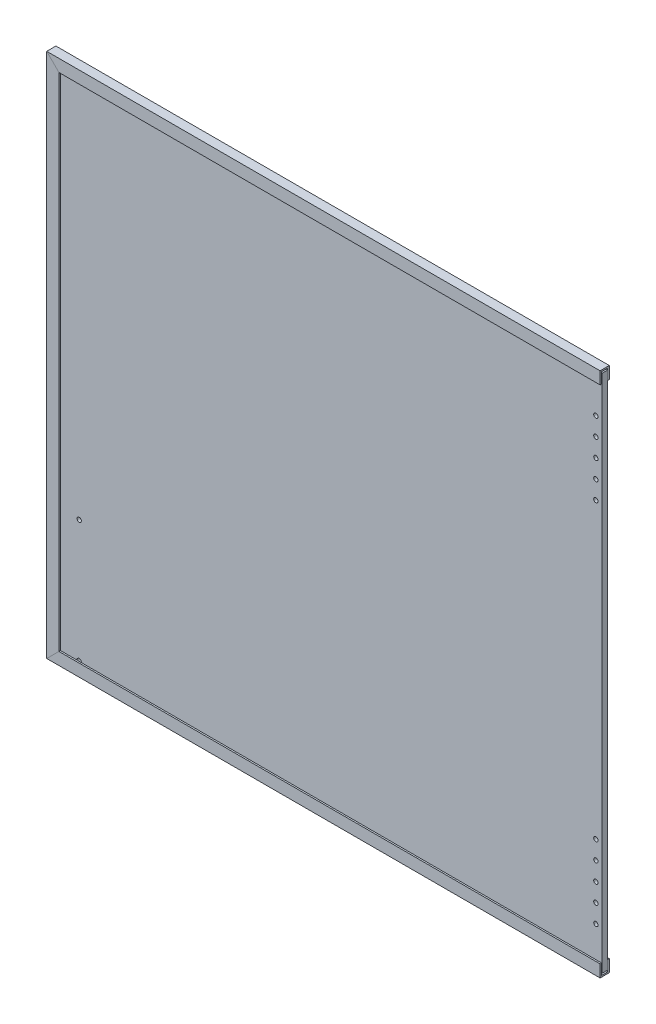
SolidWorks part; units mm, degrees
material "PC High Viscosity"
ref_plane "Front Plane" through (0, 0, 0) normal (0, 0, 1) x (1, 0, 0)
ref_plane "Top Plane" through (0, 0, 0) normal (0, 1, 0) x (1, 0, 0)
ref_plane "Right Plane" through (0, 0, 0) normal (1, 0, 0) x (0, 0, -1)
sketch "Shelf opening" plane through (0, 0, 0) normal (0, 0, 1) x (1, 0, 0)
  line L1 (0, 0) -> (577.85, 0)
  line L2 (0, 0) -> (0, 520.7)
  line L3 (0, 520.7) -> (577.85, 520.7)
  line L4 (577.85, 0) -> (577.85, 520.7)
  dimension "D1" = 577.85
  dimension "D2" = 520.7
sketch "Sketch2" plane through (0, 0, 0) normal (0, 0, 1) x (1, 0, 0)
  line L0 (577.85, 0) -> (577.85, 520.7) construction
  line L1 (3.175, 533.4) -> (577.85, 533.4)
  line L2 (3.175, 533.4) -> (3.175, -12.7)
  line L3 (3.175, -12.7) -> (577.85, -12.7)
  line L4 (577.85, 533.4) -> (577.85, -12.7)
  line L5 (0, 520.7) -> (577.85, 520.7) construction
  line L6 (0, 0) -> (0, 520.7) construction
  line L7 (0, 0) -> (577.85, 0) construction
  dimension "D1" = 12.7
  dimension "D2" = 3.175
  dimension "D3" = 12.7
extrude "Frame outer dimensions" add sketch "Sketch2" along normal mid plane 9.525
sketch "Sketch3" plane through (0, 0, 4.7625) normal (0, 0, 1) x (1, 0, 0)
  line L0 (577.85, -12.7) -> (577.85, 533.4) construction
  line L1 (577.85, 520.7) -> (15.875, 520.7)
  line L2 (577.85, 520.7) -> (577.85, 0)
  line L3 (577.85, 0) -> (15.875, 0)
  line L4 (15.875, 520.7) -> (15.875, 0)
  line L5 (577.85, 533.4) -> (3.175, 533.4) construction
  line L6 (3.175, 533.4) -> (3.175, -12.7) construction
  line L7 (3.175, -12.7) -> (577.85, -12.7) construction
  dimension "D1" = 12.7
  dimension "D2" = 12.7
  dimension "D3" = 12.7
extrude "Frame inner dimensions" cut sketch "Sketch3" against normal through all
sketch "Sketch4" plane through (0, 0, 0) normal (0, 0, 1) x (1, 0, 0)
  line L0 (577.85, 520.7) -> (577.85, 533.4) construction
  line L1 (577.85, 531.8125) -> (4.7625, 531.8125)
  line L2 (577.85, 531.8125) -> (577.85, -11.1125)
  line L3 (577.85, -11.1125) -> (4.7625, -11.1125)
  line L4 (4.7625, 531.8125) -> (4.7625, -11.1125)
  line L5 (577.85, 533.4) -> (3.175, 533.4) construction
  line L6 (3.175, 533.4) -> (3.175, -12.7) construction
  line L7 (3.175, -12.7) -> (577.85, -12.7) construction
  dimension "D1" = 1.5875
  dimension "D2" = 1.5875
  dimension "D3" = 1.5875
extrude "Frame profile" cut sketch "Sketch4" along normal offset from surface 1.5875 and the other way offset from surface (3.175 mm away) 1.5875 up to face at (293.6875, 260.35, 4.7625) other way up to face at (293.6875, 260.35, -4.7625)
sketch "Frame sections" plane through (0, 0, 4.7625) normal (0, 0, 1) x (1, 0, 0)
  line L0 (3.175, 533.4) -> (15.875, 520.7)
  line L1 (3.175, -12.7) -> (15.875, 0)
split "Frame section split" trim tools "Frame sections" bodies to split 103 resulting bodies 105 106 107
sketch "Sketch5" plane through (0, 0, 0) normal (0, 0, 1) x (1, 0, 0)
  line L0 (577.85, 520.7) -> (577.85, 533.4) construction
  line L1 (577.85, 530.225) -> (6.35, 530.225)
  line L2 (577.85, 530.225) -> (577.85, -9.525)
  line L3 (577.85, -9.525) -> (6.35, -9.525)
  line L4 (6.35, 530.225) -> (6.35, -9.525)
  line L5 (4.7625, 531.8125) -> (577.85, 531.8125) construction
  line L6 (4.7625, -11.1125) -> (4.7625, 531.8125) construction
  line L7 (577.85, -11.1125) -> (4.7625, -11.1125) construction
  dimension "D1" = 1.5875
  dimension "D2" = 1.5875
  dimension "D3" = 1.5875
  dimension "D4" = 571.5
  dimension "D5" = 539.75
extrude "Door panel" add sketch "Sketch5" along normal mid plane 5.588 separate body
sketch "Hinge positions" plane through (0, 0, 2.794) normal (0, 0, 1) x (1, 0, 0)
  line L0 (577.85, -9.525) -> (577.85, 530.225) construction
  line L1 (577.85, 498.475) -> (565.15, 498.475)
  line L2 (577.85, 498.475) -> (577.85, 403.225)
  line L3 (577.85, 403.225) -> (565.15, 403.225)
  line L4 (565.15, 498.475) -> (565.15, 403.225)
  line L5 (565.15, 117.475) -> (577.85, 117.475)
  line L6 (565.15, 117.475) -> (565.15, 22.225)
  line L7 (565.15, 22.225) -> (577.85, 22.225)
  line L8 (577.85, 117.475) -> (577.85, 22.225)
  line L10 (0, 0) -> (577.85, 0) construction
  line L11 (0, 520.7) -> (577.85, 520.7) construction
  dimension "D1" = 95.25
  dimension "D2" = 12.7
  dimension "D3" = 22.225
  dimension "D4" = 22.225
  dimension "D5" = 381
sketch "Sketch8" plane through (0, 0, 2.794) normal (0, 0, 1) x (1, 0, 0)
  line L0 (565.15, 69.85) -> (577.85, 69.85) construction
  line L2 (565.15, 117.475) -> (565.15, 22.225) construction
  line L3 (577.85, 117.475) -> (577.85, 22.225) construction
  line L4 (565.15, 450.85) -> (577.85, 450.85) construction
  line L6 (565.15, 498.475) -> (565.15, 403.225) construction
  line L7 (577.85, 498.475) -> (577.85, 403.225) construction
  point P0 (571.5, 31.75)
  point P11 (571.5, 50.8)
  point P12 (571.5, 69.85)
  point P13 (571.5, 88.9)
  point P14 (571.5, 107.95)
  point P15 (571.5, 431.8)
  point P16 (571.5, 450.85)
  point P17 (571.5, 469.9)
  point P18 (571.5, 488.95)
  point P19 (571.5, 412.75)
  dimension "D3" = 19.05
  dimension "D1" = 5
  dimension "D2" = 2
hole_wizard "#8 Clearance Hole1" positions "Sketch8" profile "Sketch9" hole size "#8" standard "ANSI Inch" end condition through all
sketch "Sketch9" plane through (571.5, 31.75, 2.794) normal (1, 0, 0) x (0, -1, 0)
  line L0 (0, 0) -> (0, 7.5565)
  line L1 (0, 7.5565) -> (2.2479, 7.5565)
  line L2 (2.2479, 7.5565) -> (2.2479, 0)
  line L5 (2.2479, 0) -> (0, 0)
  line L11 (0, -6.35) -> (0, 107.95) construction
  dimension "Thru Hole Dia." = 4.4958
  dimension "Thru Hole Depth" = 7.5565
sketch "Handle positions" plane through (0, 0, 2.794) normal (0, 0, 1) x (1, 0, 0)
  line L0 (6.35, 530.225) -> (6.35, -9.525) construction
  line L1 (6.35, -9.525) -> (44.45, -9.525)
  line L2 (6.35, -9.525) -> (6.35, 139.7)
  line L3 (6.35, 139.7) -> (44.45, 139.7)
  line L4 (44.45, -9.525) -> (44.45, 139.7)
  line L5 (6.35, 530.225) -> (44.45, 530.225)
  line L6 (6.35, 530.225) -> (6.35, 381)
  line L7 (6.35, 381) -> (44.45, 381)
  line L8 (44.45, 530.225) -> (44.45, 381)
  line L9 (6.35, -9.525) -> (577.85, -9.525) construction
  line L10 (577.85, 530.225) -> (6.35, 530.225) construction
  dimension "D1" = 149.225
  dimension "D2" = 38.1
sketch "Sketch11" plane through (0, 0, 2.794) normal (0, 0, 1) x (1, 0, 0)
  line L0 (34.925, 127) -> (34.925, 0) construction
  line L2 (6.35, -9.525) -> (6.35, 139.7) construction
  line L3 (6.35, -9.525) -> (44.45, -9.525) construction
  point P0 (34.925, 0)
  point P2 (34.925, 127)
  dimension "D1" = 28.575
  dimension "D2" = 9.525
  dimension "D3" = 136.525
hole_wizard "#8 Clearance Hole2" positions "Sketch11" profile "Sketch12" hole size "#8" standard "ANSI Inch" end condition through all
sketch "Sketch12" plane through (34.925, 0, 2.794) normal (1, 0, 0) x (0, -1, 0)
  line L0 (0, 0) -> (0, 7.5565)
  line L1 (0, 7.5565) -> (2.2479, 7.5565)
  line L2 (2.2479, 7.5565) -> (2.2479, 0)
  line L5 (2.2479, 0) -> (0, 0)
  line L11 (0, -6.35) -> (0, 107.95) construction
  dimension "Thru Hole Dia." = 4.4958
  dimension "Thru Hole Depth" = 7.5565
hole_wizard "#8 Clearance Hole3" [suppressed] positions "Sketch13" profile "Sketch14" hole size "#8" standard "ANSI Inch"
sketch "Sketch13" plane through (0, 0, 2.794) normal (0, 0, 1) x (1, 0, 0)
  line L0 (34.925, 520.7) -> (34.925, 393.7) construction
  line L2 (6.35, 530.225) -> (6.35, 381) construction
  line L3 (6.35, 530.225) -> (44.45, 530.225) construction
  point P0 (34.925, 520.7)
  point P2 (34.925, 393.7)
  dimension "D1" = 28.575
  dimension "D2" = 9.525
  dimension "D3" = 136.525
sketch "Sketch14" plane through (34.925, 520.7, 2.794) normal (1, 0, 0) x (0, -1, 0)
  line L0 (0, 0) -> (0, 7.5565)
  line L1 (0, 7.5565) -> (2.2479, 7.5565)
  line L2 (2.2479, 7.5565) -> (2.2479, 0)
  line L5 (2.2479, 0) -> (0, 0)
  line L11 (0, -6.35) -> (0, 107.95) construction
  dimension "Thru Hole Dia." = 4.4958
  dimension "Thru Hole Depth" = 7.5565
mirror "Mirror1" about plane through (0, 0, 0) normal (1, 0, 0) of bodies 105 106 107 113 108
delete or keep bodies "Body-Delete/Keep 1" type keep bodies bodies 105 106 107 113
delete or keep bodies "Body-Delete/Keep 2" [suppressed] type keep bodies bodies 109 110 111 112
